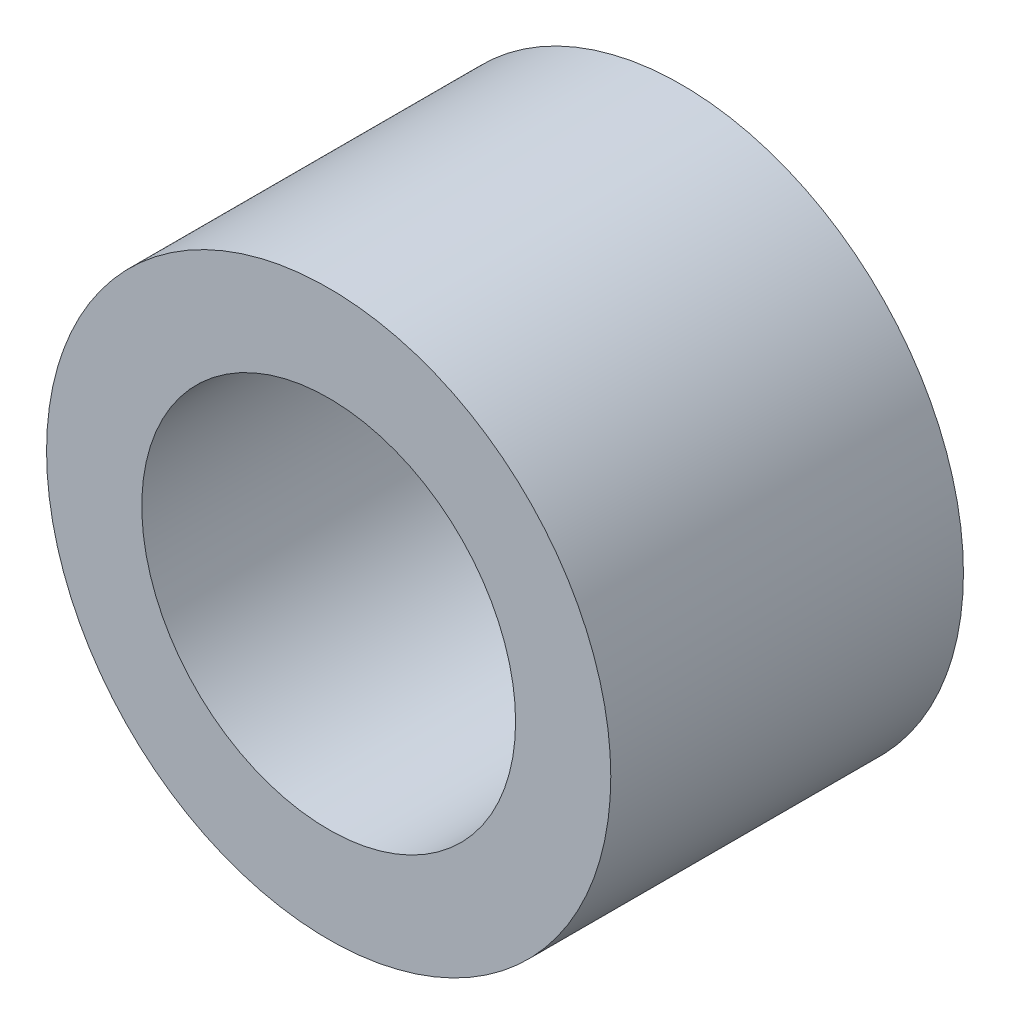
SolidWorks part; units mm, degrees
ref_plane "Front Plane" through (0, 0, 0) normal (0, 0, 1) x (1, 0, 0)
ref_plane "Top Plane" through (0, 0, 0) normal (0, 1, 0) x (1, 0, 0)
ref_plane "Right Plane" through (0, 0, 0) normal (1, 0, 0) x (0, 0, -1)
sketch "Sketch1" plane through (0, 0, 0) normal (0, 0, 1) x (1, 0, 0)
  circle A0 centre (0, 0) radius 4
  circle A1 centre (0, 0) radius 2.65
  dimension "OD" = 8
  dimension "ID" = 5.3
extrude "Extrude1" add sketch "Sketch1" along normal mid plane 5
sketch "Sketch2" plane through (0, 0, 0) normal (1, 0, 0) x (0, 0, -1)
  line L0 (-2.5, -2.65) -> (2.5, -2.65) construction
  line L3 (2.5, 2.65) -> (-2.5, 2.65) construction
  line L5 (-2.5, -2.65) -> (2.5, -2.65)
  line L6 (2.5, 2.65) -> (-2.5, 2.65)
sketch "Sketch4" plane through (0, 0, 2.5) normal (0, 0, 1) x (1, 0, 0)
  line L0 (0, 0) -> (-1.8738, 1.8738)
  line L1 (0, -1.1) -> (0, 1.1) construction
  circle A0 centre (0, 0) radius 2.65 construction
  dimension "D1" = 45
